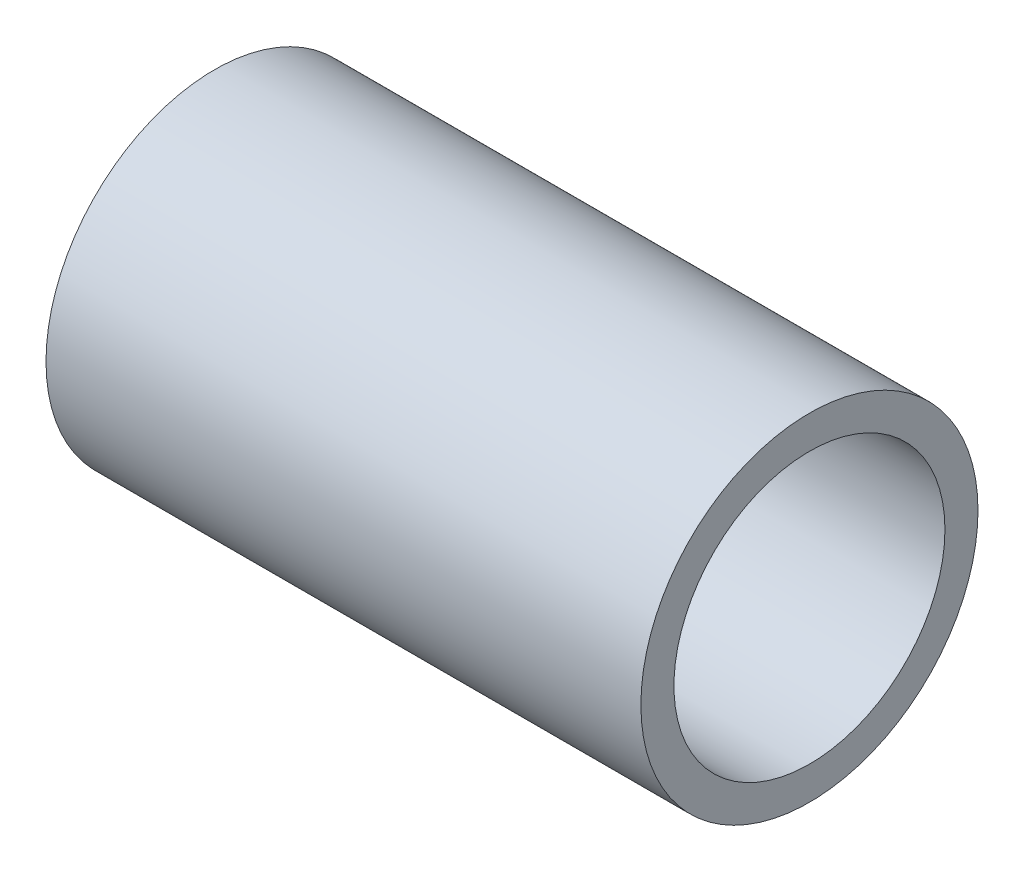
SolidWorks part; units mm, degrees
ref_plane "Vorne" through (0, 0, 0) normal (0, 0, 1) x (1, 0, 0)
ref_plane "Oben" through (0, 0, 0) normal (0, 1, 0) x (1, 0, 0)
ref_plane "Seite" through (0, 0, 0) normal (1, 0, 0) x (0, 0, -1)
sketch "Skizze1" plane through (0, 0, 0) normal (1, 0, 0) x (0, 0, -1)
  circle A0 centre (0, 0) radius 2.05
  circle A1 centre (0, 0) radius 2.55
  dimension "D1" = 4.1
  dimension "D2" = 5.1
extrude "Aufsatz-Linear austragen1" add sketch "Skizze1" along normal blind 9
